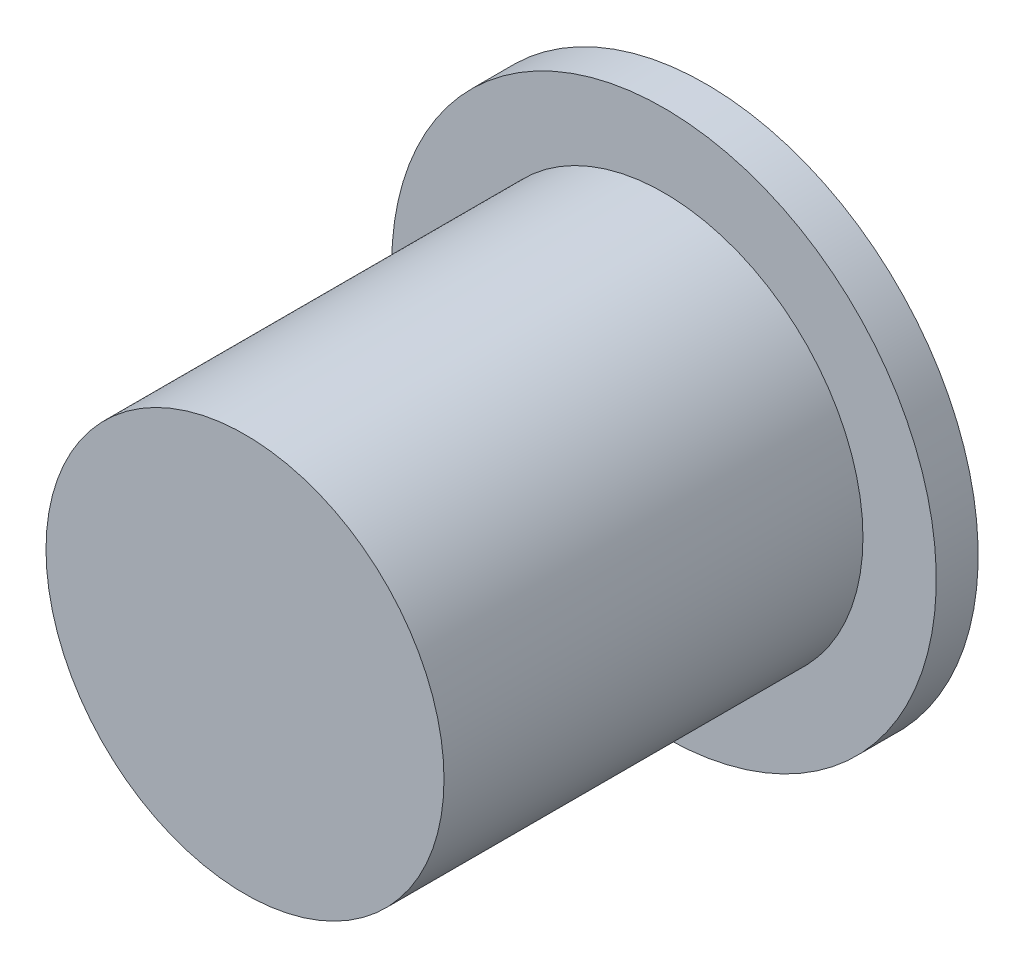
SolidWorks part; units mm, degrees
ref_plane "Front Plane" through (0, 0, 0) normal (0, 0, 1) x (1, 0, 0)
ref_plane "Top Plane" through (0, 0, 0) normal (0, 1, 0) x (1, 0, 0)
ref_plane "Right Plane" through (0, 0, 0) normal (1, 0, 0) x (0, 0, -1)
sketch "Sketch1" plane through (0, 0, 0) normal (0, 0, 1) x (1, 0, 0)
  circle A0 centre (0, 0) radius 2.375
  dimension "D1" = 4.75
extrude "Boss-Extrude1" add sketch "Sketch1" along normal blind 5
sketch "Sketch3" plane through (0, 0, 0) normal (0, 0, -1) x (-1, 0, 0)
  circle A0 centre (0, 0) radius 3.25
  dimension "D1" = 6.5
extrude "Boss-Extrude2" add sketch "Sketch3" along normal blind 0.5
sketch "Sketch5" plane through (0, 0, -0.5) normal (0, 0, -1) x (-1, 0, 0)
  circle A0 centre (0, 0) radius 1.75
  dimension "D1" = 3.5
extrude "Cut-Extrude1" cut sketch "Sketch5" against normal blind 0.25
